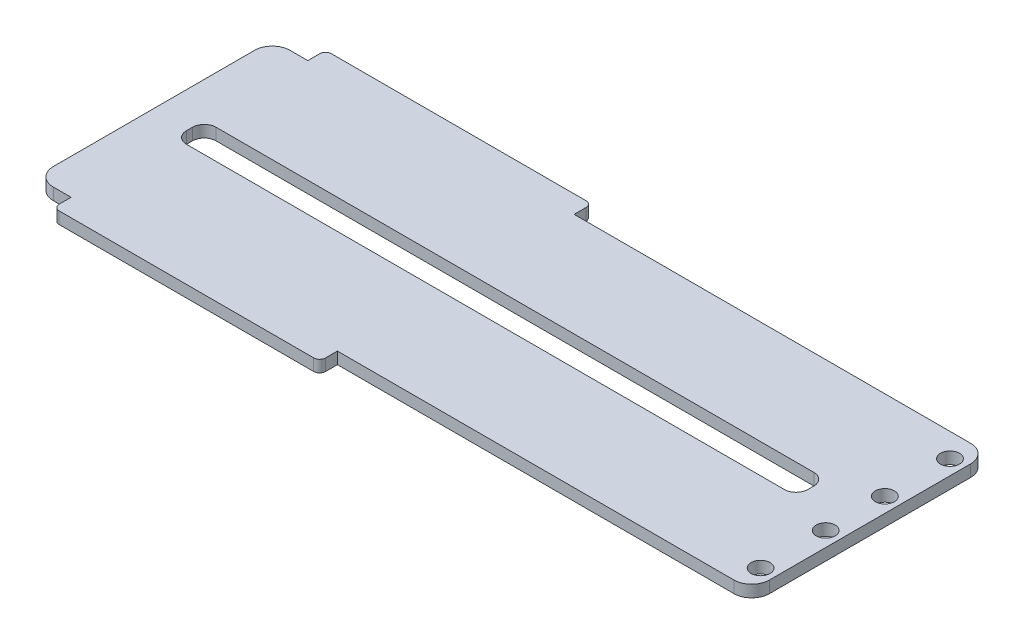
SolidWorks part; units mm, degrees
ref_plane "前视基准面" through (0, 0, 0) normal (0, 0, 1) x (1, 0, 0)
ref_plane "上视基准面" through (0, 0, 0) normal (0, 1, 0) x (1, 0, 0)
ref_plane "右视基准面" through (0, 0, 0) normal (1, 0, 0) x (0, 0, -1)
sketch "草图1" plane through (0, 0, 0) normal (0, 1, 0) x (1, 0, 0)
  line L1 (-62.5, -20) -> (62.5, -20)
  line L2 (-62.5, -20) -> (-62.5, 20)
  line L3 (-62.5, 20) -> (62.5, 20)
  line L4 (62.5, -20) -> (62.5, 20)
  line L5 (-62.5, -20) -> (62.5, 20) construction
  line L6 (-62.5, 20) -> (62.5, -20) construction
  line L7 (-52.5, -20) -> (-7.5, -20)
  line L8 (-52.5, -20) -> (-52.5, -23)
  line L9 (-52.5, -23) -> (-7.5, -23)
  line L10 (-7.5, -20) -> (-7.5, -23)
  line L11 (-52.5, 20) -> (-7.5, 20)
  line L12 (-52.5, 20) -> (-52.5, 23)
  line L13 (-52.5, 23) -> (-7.5, 23)
  line L14 (-7.5, 20) -> (-7.5, 23)
  line L15 (-50.5, -2.5) -> (50.5, -2.5)
  line L16 (-52.5, -0.5) -> (-52.5, 0.5)
  line L17 (-50.5, 2.5) -> (50.5, 2.5)
  line L18 (52.5, -0.5) -> (52.5, 0.5)
  line L19 (-52.5, -2.5) -> (52.5, 2.5) construction
  line L20 (-52.5, 2.5) -> (52.5, -2.5) construction
  circle A0 centre (60, 16) radius 1.6
  circle A1 centre (60, 5) radius 1.6
  circle A2 centre (60, -5) radius 1.6
  circle A3 centre (60, -16) radius 1.6
  arc A4 (50.5, -2.5) -> (52.5, -0.5) centre (50.5, -0.5) ccw
  arc A5 (50.5, 2.5) -> (52.5, 0.5) centre (50.5, 0.5) cw
  arc A6 (-50.5, -2.5) -> (-52.5, -0.5) centre (-50.5, -0.5) cw
  arc A7 (-52.5, 0.5) -> (-50.5, 2.5) centre (-50.5, 0.5) cw
  point P0 (0, 0)
  point P22 (0, 0)
  dimension "D9" = 2
  dimension "D1" = 125
  dimension "D2" = 40
  dimension "D3" = 3
  dimension "D4" = 3
  dimension "D5" = 10
  dimension "D6" = 10
  dimension "D7" = 45
  dimension "D8" = 45
extrude "凸台-拉伸1" add sketch "草图1" along normal blind 2 contours L1 L4 L3 L2 A3 A2 A1 A0 | L3 L14 L13 L12 | L10 L1 L8 L9
sketch "草图2" plane through (0, 2, 0) normal (0, 1, 0) x (1, 0, 0)
  line L1 (-62.5, 20) -> (-58.5, 20)
  line L2 (-62.5, 20) -> (-62.5, -20)
  line L3 (-62.5, -20) -> (-58.5, -20)
  line L4 (-58.5, 20) -> (-58.5, -20)
extrude "切除-拉伸1" cut sketch "草图2" against normal blind 10
fillet "圆角1" radius 3 4 edges at (62.5, 1, 20) (62.5, 1, -20) (-58.5, 1, -20) (-58.5, 1, 20)
fillet "圆角2" radius 1 4 edges at (-52.5, 1, 23) (-7.5, 1, 23) (-7.5, 1, -23) (-52.5, 1, -23)
